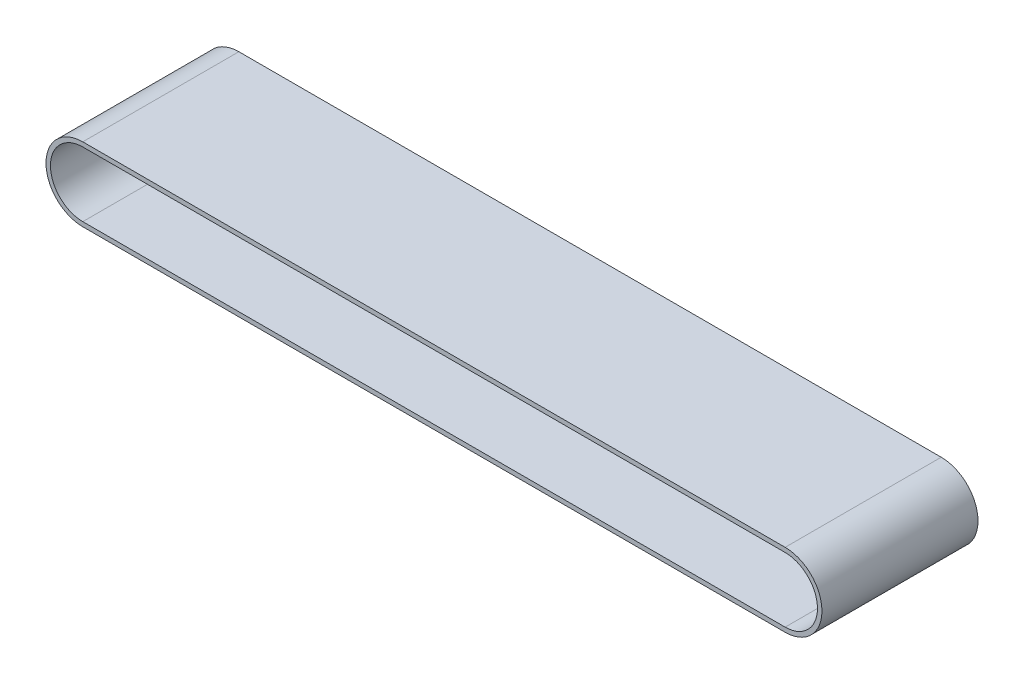
SolidWorks part; units mm, degrees
material "BUTYL"
ref_plane "Alzado" through (0, 0, 0) normal (0, 0, 1) x (1, 0, 0)
ref_plane "Planta" through (0, 0, 0) normal (0, 1, 0) x (1, 0, 0)
ref_plane "Vista lateral" through (0, 0, 0) normal (1, 0, 0) x (0, 0, -1)
sketch "Croquis2" plane through (0, 0, 0) normal (0, 0, 1) x (1, 0, 0)
  line L0 (0, 0) -> (1, 0) construction
  line L1 (0, 0) -> (0, 1) construction
  line L6 (0, 14.5) -> (315, 14.5)
  line L7 (315, -14.5) -> (0, -14.5)
  arc A1 (0, -14.5) -> (0, 14.5) centre (0, 0) cw
  arc A3 (315, 14.5) -> (315, -14.5) centre (315, 0) cw
extrude "Extruir-Lámina1" add sketch "Croquis2" along normal mid plane 70 thin thin type one direction wall 2
